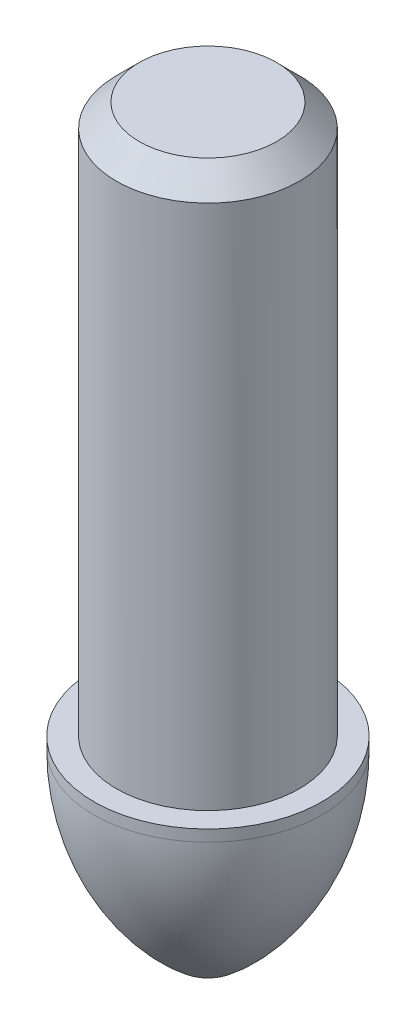
SolidWorks part; units mm, degrees
material "K110"
ref_plane "Front Plane" through (0, 0, 0) normal (0, 0, 1) x (1, 0, 0)
ref_plane "Top Plane" through (0, 0, 0) normal (0, 1, 0) x (1, 0, 0)
ref_plane "Right Plane" through (0, 0, 0) normal (1, 0, 0) x (0, 0, -1)
sketch "Sketch1" plane through (0, 0, 0) normal (0, 0, 1) x (1, 0, 0)
  line L0 (0, 0) -> (0, -38.1343) construction
  line L1 (0, 0) -> (4, 0)
  line L2 (4, 0) -> (4, -24)
  line L3 (4, -24) -> (4.985, -24)
  line L4 (4.985, -24) -> (4.985, -24.5)
  line L5 (4.985, -24.5) -> (-4.985, -24.5) construction
  line L6 (0, -32.7186) -> (0, 0)
  arc A1 (1.2509, -32.2791) -> (4.985, -24.5) centre (-4.985, -24.5) ccw
  arc A2 (0, -32.7186) -> (1.2509, -32.2791) centre (0, -30.7186) ccw
  arc A3 (0, -28.7186) -> (0, -32.7186) centre (0, -30.7186) ccw construction
  arc A4 (1.2509, -32.2791) -> (0, -28.7186) centre (0, -30.7186) ccw construction
  arc A5 (0, -33.1343) -> (1.2509, -32.2791) centre (-4.985, -24.5) ccw construction
  dimension "D6" = 2
  dimension "D1" = 9.97
  dimension "PilotDiameter" = 9.97
  dimension "D2" = 8
  dimension "D4" = 9.97
  dimension "ShankLength" = 24.5
  dimension "D3" = 0.5
  dimension "D5" = 5
revolve "Revolve1" add sketch "Sketch1" angle 360 about L0
chamfer "Chamfer1" distance 1 angle 45 1 edges at (-4, 0, 0)
cosmetic thread "Cosmetic Thread2" parameters "D1"=16, "D2"=6.619
equation "\"D4@Sketch1\" = \"PilotDiameter@Sketch1\""
equation "\"Pierce Punch Diameter\"= 10"
equation "\"PilotDiameter@Sketch1\" = \"Pierce Punch Diameter\" - 0.03 * \"Material Thickness\""
equation "\"Material Thickness\"= 1mm"
equation "\"Punch Height\"= 20mm"
equation "\"ShankLength@Sketch1\"= \"Punch Height\" + \"Thread into Punch Holder\" + \"Pilot Engagement Length\" - 6"
equation "\"Thread into Punch Holder\"= 10mm"
equation "\"Pilot Engagement Length\"= \"Material Thickness\" * 0.5"
equation "\"D3@Sketch1\"= \"Pilot Engagement Length\""
equation "\"D6@Sketch1\"= Round ( \"PilotDiameter@Sketch1\" * 0.25 )"
